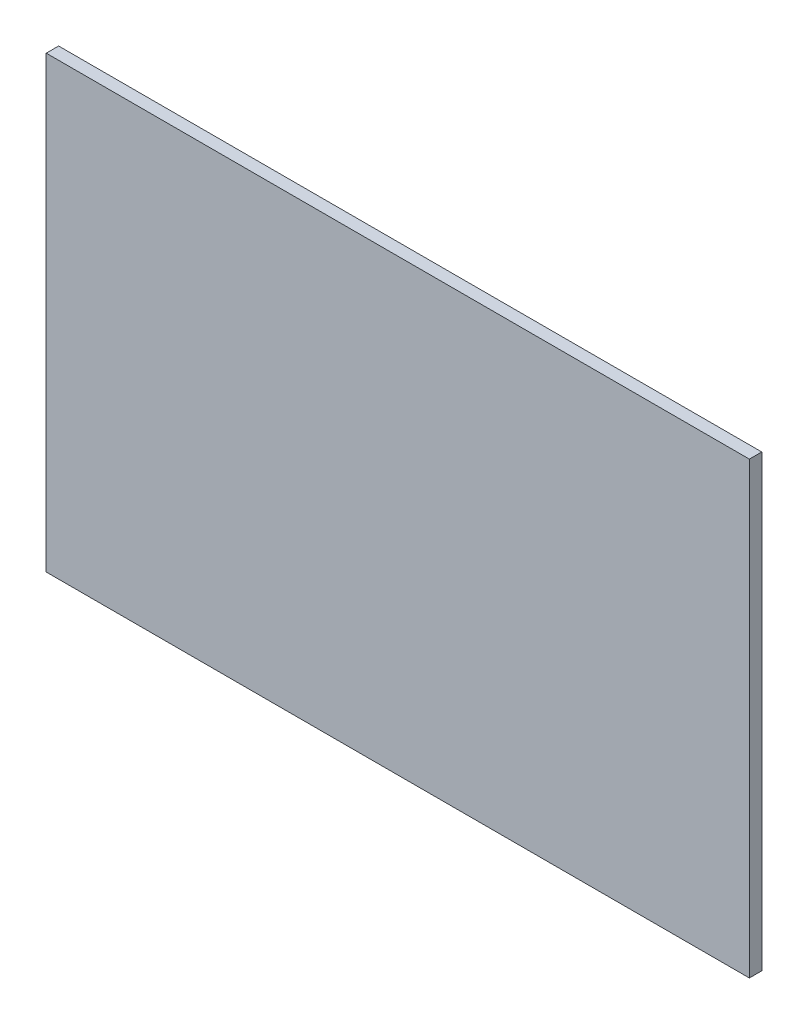
SolidWorks part; units mm, degrees
ref_plane "Front" through (0, 0, 0) normal (0, 0, 1) x (1, 0, 0)
ref_plane "Top" through (0, 0, 0) normal (0, 1, 0) x (1, 0, 0)
ref_plane "Right" through (0, 0, 0) normal (1, 0, 0) x (0, 0, -1)
sketch "Sketch1" plane through (0, 0, 0) normal (0, 0, 1) x (1, 0, 0)
  line L1 (72.0108, -46.0231) -> (-72.0108, -46.0231)
  line L2 (72.0108, -46.0231) -> (72.0108, 46.0231)
  line L3 (72.0108, 46.0231) -> (-72.0108, 46.0231)
  line L4 (-72.0108, -46.0231) -> (-72.0108, 46.0231)
  point P0 (0, 0)
extrude "Boss-Extrude1" add sketch "Sketch1" along normal blind 2.54
